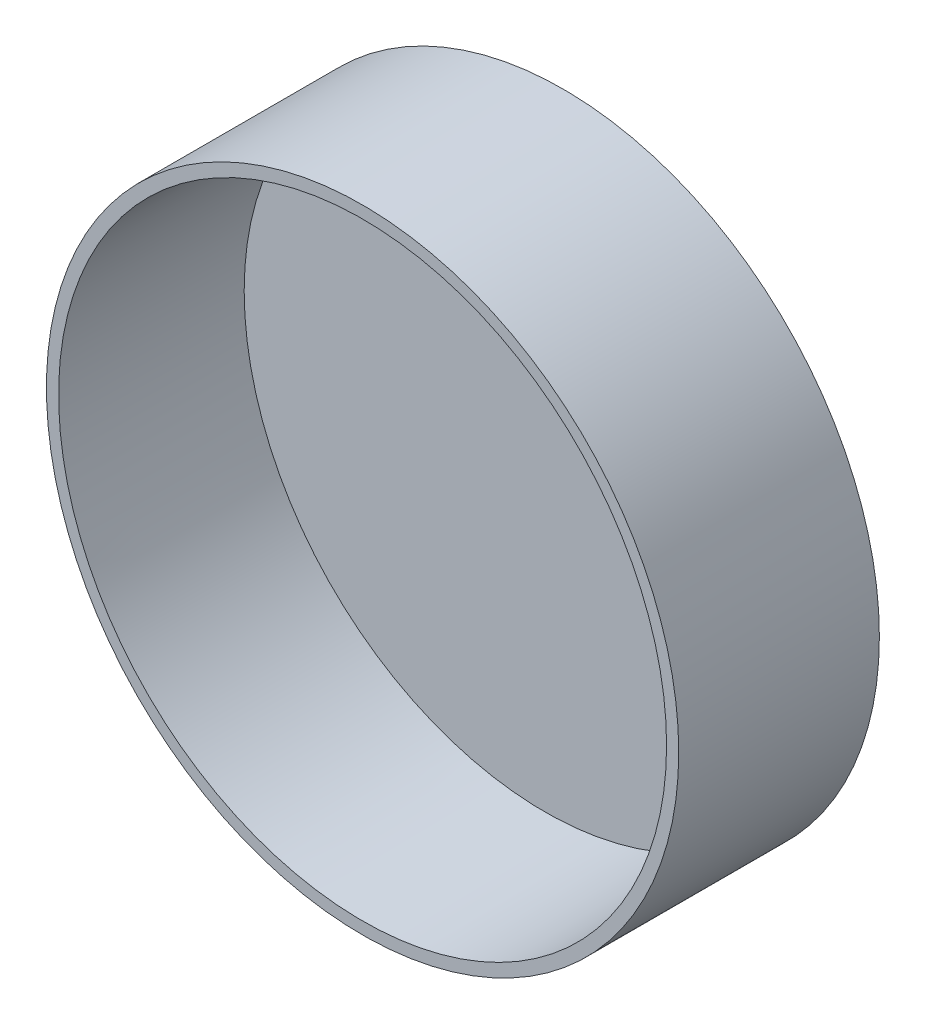
SolidWorks part; units mm, degrees
ref_plane "Plan de face" through (0, 0, 0) normal (0, 0, 1) x (1, 0, 0)
ref_plane "Plan de dessus" through (0, 0, 0) normal (0, 1, 0) x (1, 0, 0)
ref_plane "Plan de droite" through (0, 0, 0) normal (1, 0, 0) x (0, 0, -1)
sketch "Esquisse1" plane through (0, 0, 0) normal (0, 0, 1) x (1, 0, 0)
  circle A0 centre (0, 0) radius 10.4
  dimension "D1" = 20.8
extrude "Boss.-Extru.1" add sketch "Esquisse1" along normal blind 6.6
sketch "Esquisse2" plane through (0, 0, 6.6) normal (0, 0, 1) x (1, 0, 0)
  circle A0 centre (0, 0) radius 10
  dimension "D1" = 20
extrude "Enlèv. mat.-Extru.1" cut sketch "Esquisse2" against normal blind 6 draft 1
